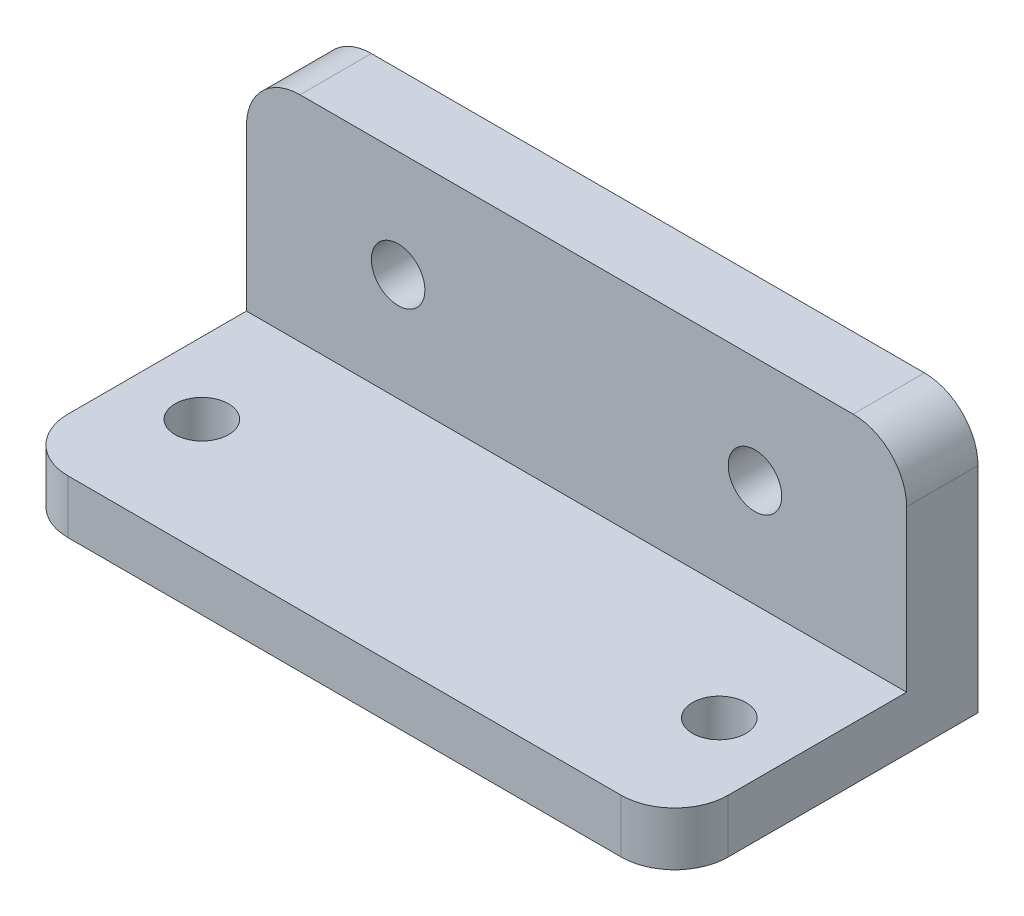
SolidWorks part; units mm, degrees
ref_plane "前视基准面" through (0, 0, 0) normal (0, 0, 1) x (1, 0, 0)
ref_plane "上视基准面" through (0, 0, 0) normal (0, 1, 0) x (1, 0, 0)
ref_plane "右视基准面" through (0, 0, 0) normal (1, 0, 0) x (0, 0, -1)
sketch "草图2" plane through (0, 0, 0) normal (0, 1, 0) x (1, 0, 0)
  line L0 (-18.5, 0) -> (18.5, 0) construction
  line L1 (-18.5, 6.5) -> (18.5, 6.5)
  line L2 (-18.5, -6.5) -> (18.5, -6.5)
  line L3 (18.5, -6.5) -> (18.5, 6.5)
  line L4 (-18.5, -6.5) -> (-18.5, 6.5)
  circle A2 centre (14.5, 0) radius 1.5
  circle A3 centre (-14.5, 0) radius 1.5
  point P2 (0, 0)
  dimension "D2" = 13
  dimension "D3" = 3
  dimension "D4" = 3
  dimension "D1" = 37
  dimension "D5" = 29
  dimension "D6" = 14.5
extrude "凸台-拉伸2" add sketch "草图2" along normal blind 3 contours L1 L3 L2 L4
sketch "草图3" plane through (0, 0, 0) normal (0, -1, 0) x (1, 0, 0)
  circle A0 centre (-14.5, 0) radius 1.5
  circle A1 centre (14.5, 0) radius 1.5
  dimension "D1" = 3
  dimension "D3" = 3
  dimension "D2" = 14.5
  dimension "D4" = 29
extrude "切除-拉伸2" cut sketch "草图3" against normal blind 3
sketch "草图4" plane through (0, 0, 0) normal (0, -1, 0) x (1, 0, 0)
  line L0 (-18.5, -6.5) -> (-18.5, -10.5)
  line L1 (-18.5, -10.5) -> (18.5, -10.5)
  line L2 (18.5, 6.5) -> (-18.5, 6.5)
  line L3 (-18.5, -6.5) -> (18.5, -6.5)
  line L5 (-18.5, -6.5) -> (18.5, -6.5)
  line L6 (18.5, -10.5) -> (18.5, -6.5)
  line L11 (-18.5, 6.5) -> (-18.5, -6.5)
  line L12 (18.5, -6.5) -> (18.5, 6.5)
  dimension "D2" = 4
  dimension "D1" = 0
extrude "凸台-拉伸3" add sketch "草图4" against normal blind 15 contours L1 L6 L5 L0
fillet "圆角4" radius 3 1 edges at (18.5, 15, -8.5)
fillet "圆角5" radius 3 1 edges at (-18.5, 15, -8.5)
sketch "草图5" plane through (0, 0, -6.5) normal (0, 0, 1) x (1, 0, 0)
  line L0 (0, 15) -> (0, 3) construction
  line L1 (-15.5, 15) -> (15.5, 15) construction
  line L2 (-18.5, 3) -> (18.5, 3) construction
  circle A1 centre (10, 9.0154) radius 1.5
  circle A2 centre (-10, 9.0154) radius 1.5
  dimension "D1" = 3
  dimension "D2" = 20
extrude "切除-拉伸3" cut sketch "草图5" against normal blind 10
fillet "圆角6" radius 3 2 edges at (18.5, 1.5, 6.5) (-18.5, 1.5, 6.5)
